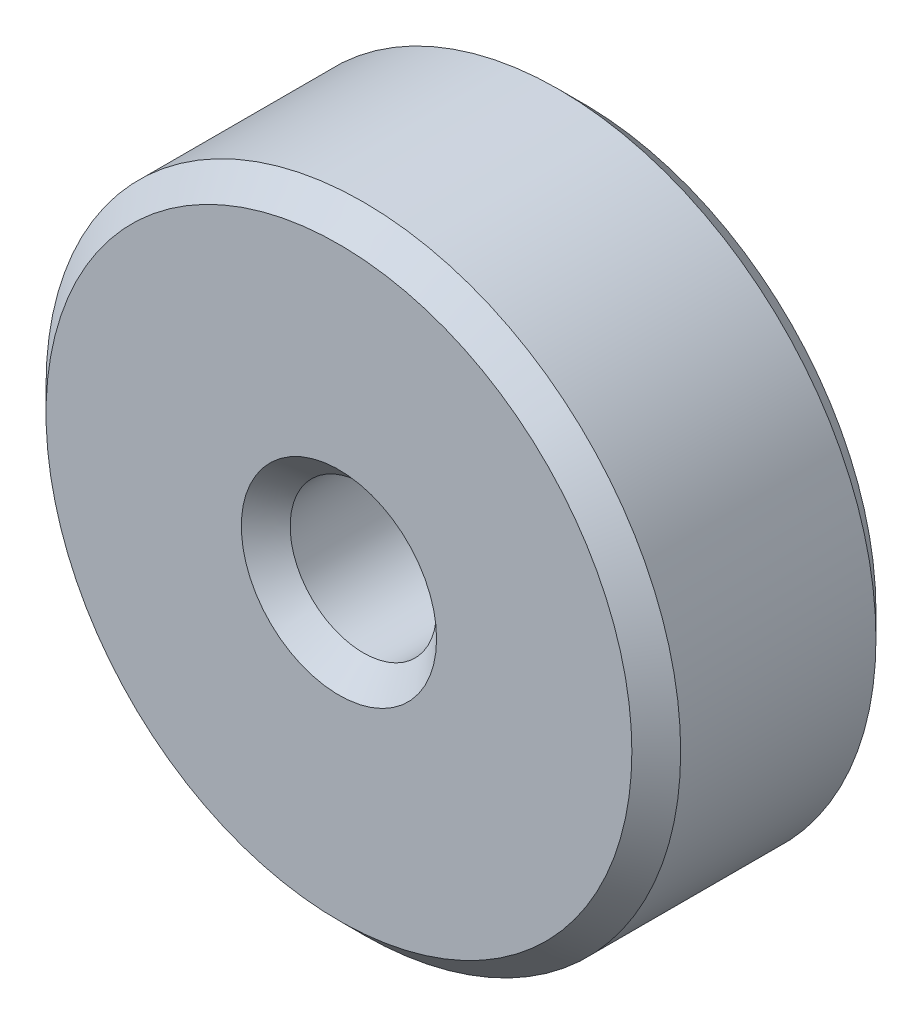
SolidWorks part; units mm, degrees
ref_plane "Front" through (0, 0, 0) normal (0, 0, 1) x (1, 0, 0)
ref_plane "Top" through (0, 0, 0) normal (0, 1, 0) x (1, 0, 0)
ref_plane "Right" through (0, 0, 0) normal (1, 0, 0) x (0, 0, -1)
sketch "Esquisse1" plane through (0, 0, 0) normal (0, 0, 1) x (1, 0, 0)
  circle A0 centre (0, 0) radius 1.5
  circle A1 centre (0, 0) radius 6.5
  dimension "D1" = 3
  dimension "D2" = 13
extrude "Boss.-Extru.1" add sketch "Esquisse1" along normal blind 5
chamfer "Chanfrein1" distance 0.5 angle 45 4 edges at (1.5, 0, 0) (6.5, 0, 0) (1.5, 0, 5) (6.5, 0, 5)
